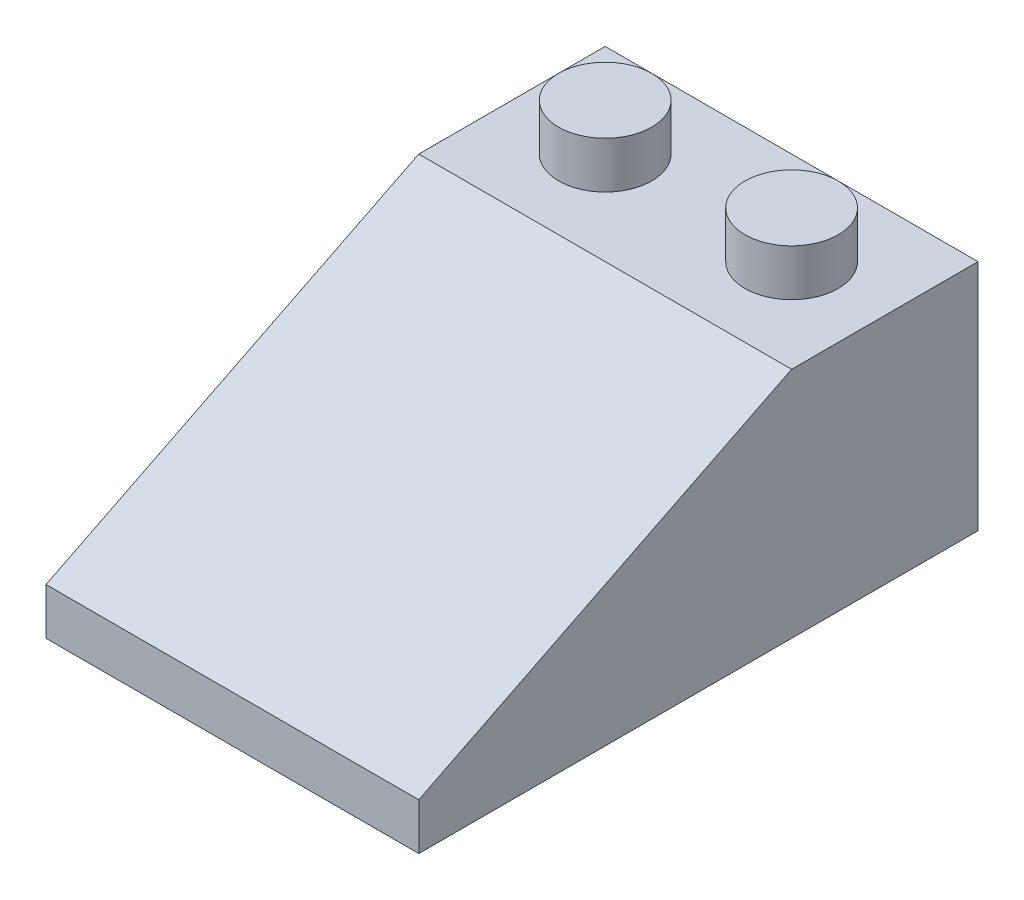
SolidWorks part; units mm, degrees
ref_plane "Front Plane" through (0, 0, 0) normal (0, 0, 1) x (1, 0, 0)
ref_plane "Top Plane" through (0, 0, 0) normal (0, 1, 0) x (1, 0, 0)
ref_plane "Right Plane" through (0, 0, 0) normal (1, 0, 0) x (0, 0, -1)
sketch "Sketch1" plane through (0, 0, 0) normal (1, 0, 0) x (0, 0, -1)
  line L0 (-24, 0) -> (0, 0)
  line L1 (0, 0) -> (0, 10)
  line L2 (0, 10) -> (-8, 10)
  line L3 (-8, 10) -> (-24, 2)
  line L4 (-24, 2) -> (-24, 0)
  dimension "D1" = 24
  dimension "D2" = 10
  dimension "D3" = 8
  dimension "D4" = 2
extrude "Boss-Extrude1" add sketch "Sketch1" along normal blind 16 contours L3 L4 L0 L1 L2
sketch "Sketch2" plane through (0, 10, 0) normal (0, 1, 0) x (1, 0, 0)
  line L0 (8, 0) -> (8, -8) construction
  line L1 (16, 0) -> (0, 0) construction
  line L2 (16, -8) -> (0, -8) construction
  line L3 (0, 0) -> (0, -8) construction
  circle A0 centre (4, -4) radius 2
  circle A1 centre (12, -4) radius 2
  dimension "D3" = 4
  dimension "D1" = 4
  dimension "D2" = 4
extrude "Boss-Extrude2" add sketch "Sketch2" along normal blind 2
shell "Shell1" thickness 1
sketch "Sketch3" plane through (0, 0, 0) normal (0, -1, 0) x (1, 0, 0)
  line L0 (8, 8) -> (8, 0) construction
  line L1 (16, 0) -> (0, 0) construction
  line L2 (0, 12) -> (16, 12) construction
  line L3 (0, 24) -> (0, 0) construction
  line L4 (16, 24) -> (16, 0) construction
  circle A0 centre (8, 8) radius 2.7
  circle A1 centre (8, 8) radius 1.7
  circle A2 centre (8, 16) radius 1.7
  circle A3 centre (8, 16) radius 2.7
  dimension "D1" = 5.4
  dimension "D2" = 3.4
  dimension "D3" = 8
extrude "Boss-Extrude4" add sketch "Sketch3" against normal up to next
